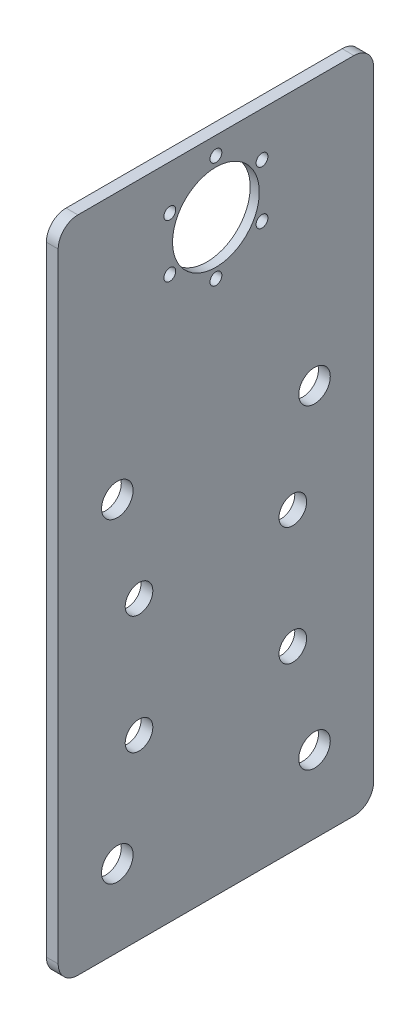
SolidWorks part; units mm, degrees
ref_plane "Front" through (0, 0, 0) normal (0, 0, 1) x (1, 0, 0)
ref_plane "Top" through (0, 0, 0) normal (0, 1, 0) x (1, 0, 0)
ref_plane "Right" through (0, 0, 0) normal (1, 0, 0) x (0, 0, -1)
sketch "Sketch1" plane through (0, 0, 0) normal (0, 0, 1) x (1, 0, 0)
  line L0 (0, -23.2805) -> (0, 106.7195)
  line L2 (3, -23.2805) -> (3, 103.7195)
  line L5 (0, -23.2805) -> (3, -23.2805)
  line L6 (0, 106.7195) -> (37, 106.7195) construction
  line L7 (3, 103.7195) -> (37, 103.7195) construction
  line L8 (0, 106.7195) -> (0, 143.7195)
  line L9 (0, 143.7195) -> (3, 143.7195)
  line L10 (3, 143.7195) -> (3, 103.7195)
  dimension "D2" = 130
  dimension "D3" = 37
  dimension "D1" = 3
extrude "Boss-Extrude1" add sketch "Sketch1" along normal mid plane 80
sketch "Sketch16" plane through (3, 0, 0) normal (1, 0, 0) x (0, 0, -1)
  line L0 (-40, -23.2805) -> (40, -23.2805) construction
  line L1 (-40, 143.7195) -> (40, 143.7195) construction
  circle A0 centre (-19.5, 21.7195) radius 3.5
  circle A1 centre (19.5, 21.7195) radius 3.5
  circle A2 centre (19.5, 51.7195) radius 3.5
  circle A3 centre (-19.5, 51.7195) radius 3.5
  circle A4 centre (25, 76.2195) radius 4
  circle A5 centre (-25, 76.2195) radius 4
  circle A6 centre (-25, -3.7805) radius 4
  circle A7 centre (25, -3.7805) radius 4
  dimension "D7" = 7
  dimension "D8" = 7
  dimension "D9" = 7
  dimension "D10" = 7
  dimension "D11" = 8
  dimension "D12" = 8
  dimension "D13" = 8
  dimension "D14" = 8
  dimension "D1" = 39
  dimension "D2" = 39
  dimension "D3" = 19.5
  dimension "D4" = 19.5
  dimension "D5" = 30
  dimension "D6" = 45
  dimension "D15" = 67.5
  dimension "D16" = 67.5
  dimension "D17" = 80
  dimension "D18" = 80
  dimension "D19" = 50
  dimension "D20" = 25
extrude "Cut-Extrude5" cut sketch "Sketch16" against normal through all
sketch "Sketch18" plane through (0, 0, 0) normal (-1, 0, 0) x (0, 0, 1)
  line L1 (40, 143.7195) -> (-40, 143.7195) construction
  line L2 (40, 143.7195) -> (40, -23.2805) construction
  circle A12 centre (0, 139.2195) radius 1.5
  circle A18 centre (0, 125.7195) radius 11
  circle A24 centre (11.6913, 132.4695) radius 1.5
  circle A25 centre (11.6913, 118.9695) radius 1.5
  circle A26 centre (0, 112.2195) radius 1.5
  circle A27 centre (-11.6913, 118.9695) radius 1.5
  circle A28 centre (-11.6913, 132.4695) radius 1.5
  point P22 (0, 125.7195)
  dimension "D3" = 22
  dimension "D5" = 3
  dimension "D1" = 0
  dimension "D2" = 4.5
  dimension "D4" = 13.5
  dimension "D6" = 40
  dimension "D7" = 6
extrude "Cut-Extrude6" cut sketch "Sketch18" against normal through all
sketch "Sketch19" plane through (0, 0, 0) normal (-1, 0, 0) x (0, 0, 1)
  line L0 (40, 143.7195) -> (-40, 143.7195) construction
  circle A0 centre (0, 125.7195) radius 16
  dimension "D1" = 18
extrude "Cut-Extrude7" cut sketch "Sketch19" against normal blind 0.7
fillet "Fillet1" radius 5 4 edges at (1.5, 143.7195, -40) (1.5, 143.7195, 40) (1.5, -23.2805, 40) (1.5, -23.2805, -40)
